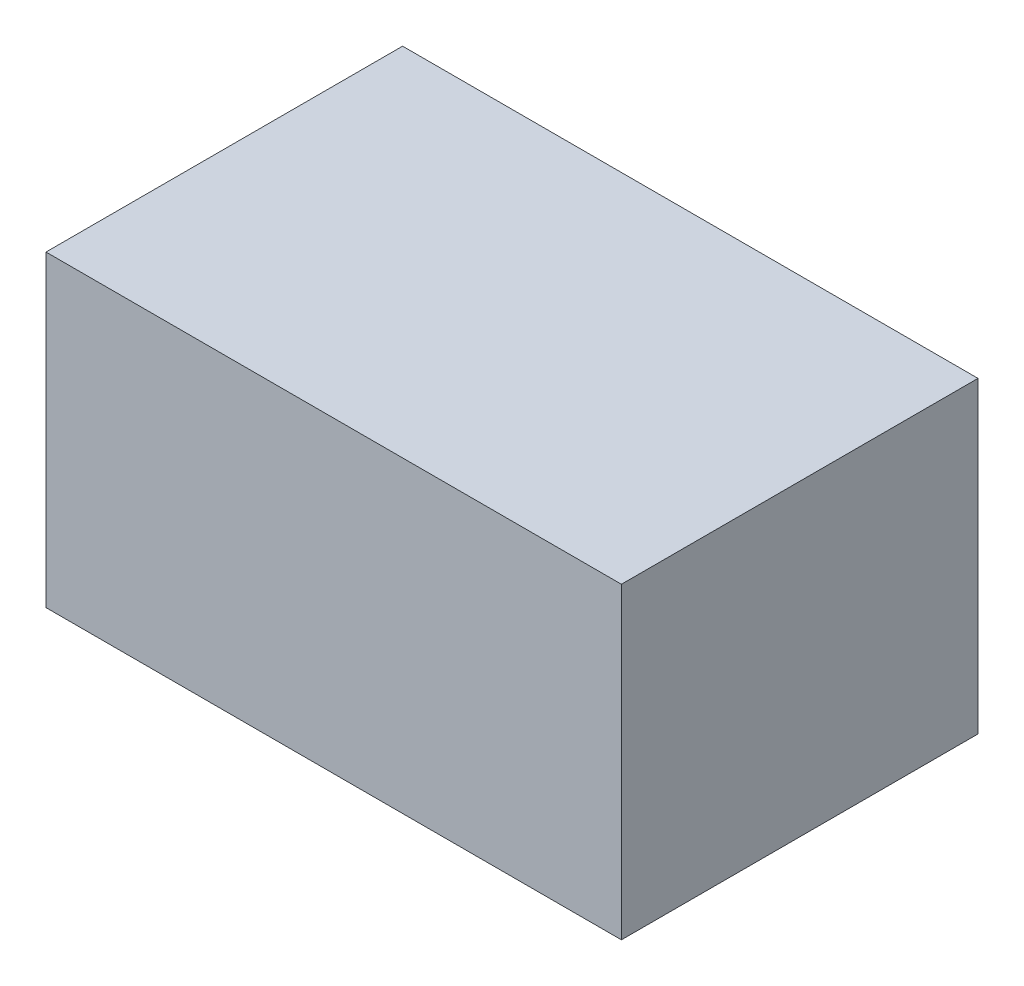
SolidWorks part; units mm, degrees
ref_plane "Front Plane" through (0, 0, 0) normal (0, 0, 1) x (1, 0, 0)
ref_plane "Top Plane" through (0, 0, 0) normal (0, 1, 0) x (1, 0, 0)
ref_plane "Right Plane" through (0, 0, 0) normal (1, 0, 0) x (0, 0, -1)
sketch "Sketch1" plane through (0, 0, 0) normal (0, 1, 0) x (1, 0, 0)
  line L1 (-355, 220) -> (355, 220)
  line L2 (-355, 220) -> (-355, -220)
  line L3 (-355, -220) -> (355, -220)
  line L4 (355, 220) -> (355, -220)
  line L5 (-355, 220) -> (355, -220) construction
  line L6 (-355, -220) -> (355, 220) construction
  point P0 (0, 0)
  dimension "D1" = 710
  dimension "D2" = 440
extrude "Boss-Extrude1" add sketch "Sketch1" along normal blind 380
equation "\"Tank_Width\" = 710mm"
equation "\"Tank_Depth\" = 440mm"
equation "\"Tank_Height\" = 380mm"
equation "\"D1@Sketch1\"=\"Tank_Width\""
equation "\"D2@Sketch1\"=\"Tank_Depth\""
equation "\"D1@Boss-Extrude1\"=\"Tank_Height\""
